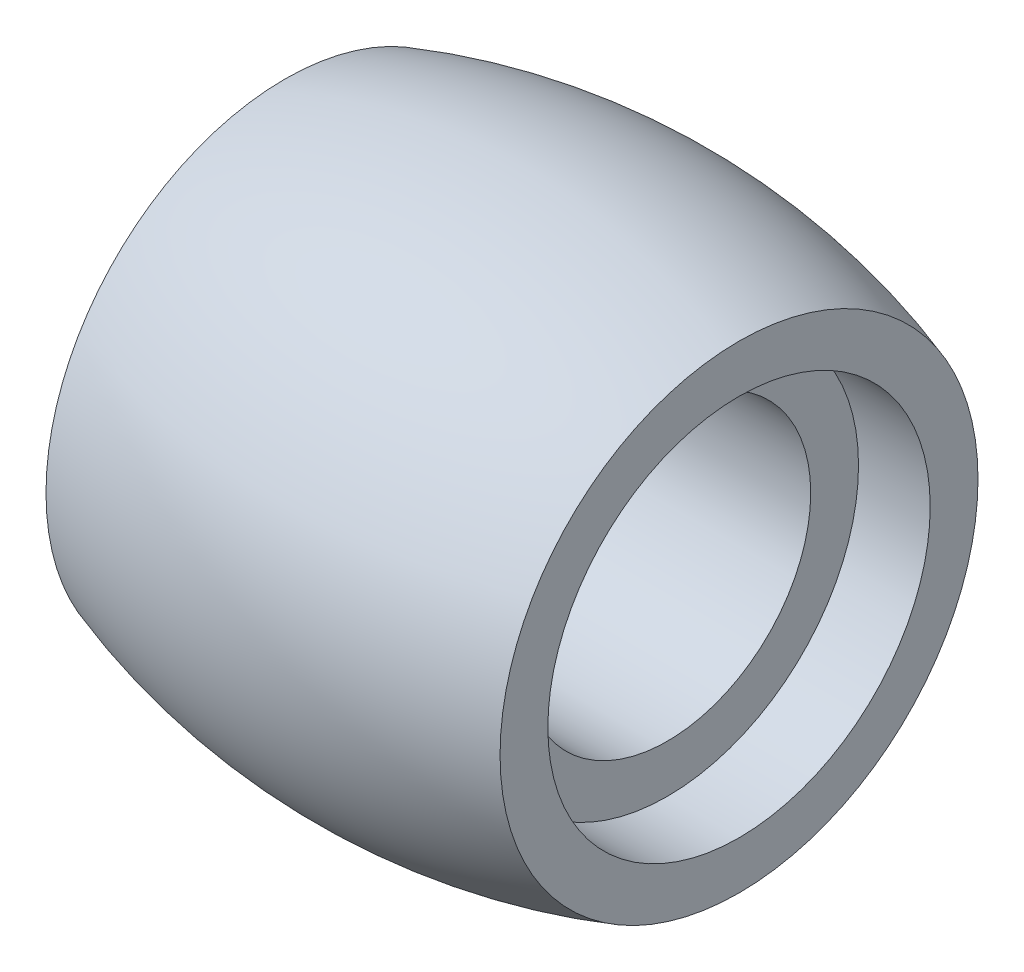
SolidWorks part; units mm, degrees
ref_plane "Front Plane" through (0, 0, 0) normal (0, 0, 1) x (1, 0, 0)
ref_plane "Top Plane" through (0, 0, 0) normal (0, 1, 0) x (1, 0, 0)
ref_plane "Right Plane" through (0, 0, 0) normal (1, 0, 0) x (0, 0, -1)
sketch "Sketch2" plane through (0, 0, 0) normal (0, 0, 1) x (1, 0, 0)
  line L0 (0, 6.5859) -> (0, -8.2148) construction
  line L1 (-8.918, 0) -> (11.5313, 0) construction
  line L2 (-3.25, 3) -> (3.25, 3)
  line L3 (3.25, 3) -> (3.25, 4)
  line L4 (3.25, 4) -> (4.75, 4)
  line L5 (4.75, 4) -> (4.75, 5)
  line L6 (-4.75, 4) -> (-4.75, 5)
  line L7 (-3.25, 4) -> (-4.75, 4)
  line L8 (-3.25, 3) -> (-3.25, 4)
  arc A0 (-4.75, 5) -> (4.75, 5) centre (0, -9.2281) cw
  point P18 (0, 3)
  dimension "D6" = 15
  dimension "1.5" = 3
  dimension "D2" = 1.5
  dimension "2.9" = 4
  dimension "D4" = 5
  dimension "D5" = 4.75
revolve "Revolve1" add sketch "Sketch2" angle 360 about L1
